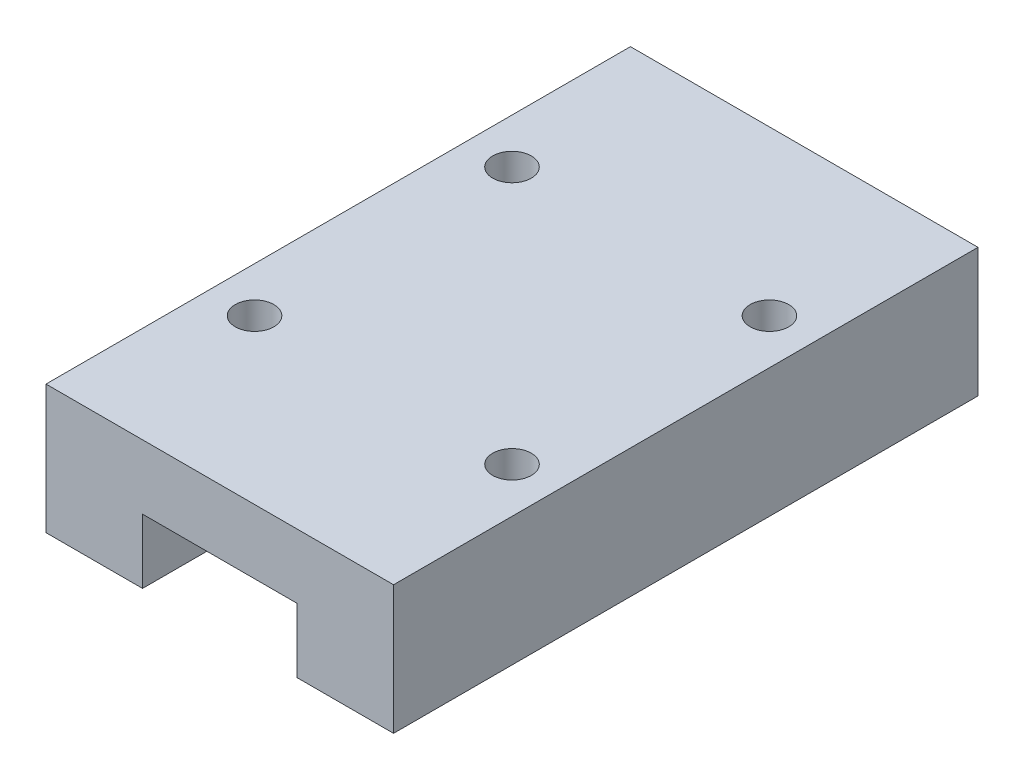
SolidWorks part; units mm, degrees
ref_plane "前视基准面" through (0, 0, 0) normal (0, 0, 1) x (1, 0, 0)
ref_plane "上视基准面" through (0, 0, 0) normal (0, 1, 0) x (1, 0, 0)
ref_plane "右视基准面" through (0, 0, 0) normal (1, 0, 0) x (0, 0, -1)
sketch "草图2" plane through (0, 0, 0) normal (0, 0, 1) x (1, 0, 0)
  line L1 (13.5, -5) -> (-13.5, -5)
  line L2 (13.5, -5) -> (13.5, 5)
  line L3 (13.5, 5) -> (-13.5, 5)
  line L4 (-13.5, -5) -> (-13.5, 5)
  line L5 (13.5, -5) -> (-13.5, 5) construction
  line L6 (13.5, 5) -> (-13.5, -5) construction
  line L7 (-6, 0) -> (6, 0)
  line L8 (-6, 0) -> (-6, -5)
  line L9 (-6, -5) -> (6, -5)
  line L10 (6, 0) -> (6, -5)
  line L11 (-6, 0) -> (6, -5) construction
  line L12 (-6, -5) -> (6, 0) construction
  point P0 (0, 0)
  point P6 (0, -2.5)
  dimension "D1" = 27
  dimension "D2" = 10
  dimension "D3" = 12
  dimension "D4" = 5
extrude "凸台-拉伸1" add sketch "草图2" along normal blind 45.4 contours L7 L10 L1 L2 L3 L4 L8
sketch "草图3" plane through (0, 5, 0) normal (0, 1, 0) x (1, 0, 0)
  line L0 (-13.5, 0) -> (13.5, -45.4) construction
  line L2 (-10, -32.7) -> (10, -32.7) construction
  line L3 (-10, -32.7) -> (-10, -12.7) construction
  line L4 (-10, -12.7) -> (10, -12.7) construction
  line L5 (10, -32.7) -> (10, -12.7) construction
  line L6 (-10, -32.7) -> (10, -12.7) construction
  line L7 (-10, -12.7) -> (10, -32.7) construction
  circle A0 centre (-10, -12.7) radius 1.5
  circle A1 centre (10, -12.7) radius 1.5
  circle A2 centre (10, -32.7) radius 1.5
  circle A3 centre (-10, -32.7) radius 1.5
  point P4 (0, -22.7)
  dimension "D3" = 3
  dimension "D4" = 3
  dimension "D5" = 3
  dimension "D6" = 3
  dimension "D1" = 20
  dimension "D2" = 20
extrude "切除-拉伸1" cut sketch "草图3" against normal blind 3.5
